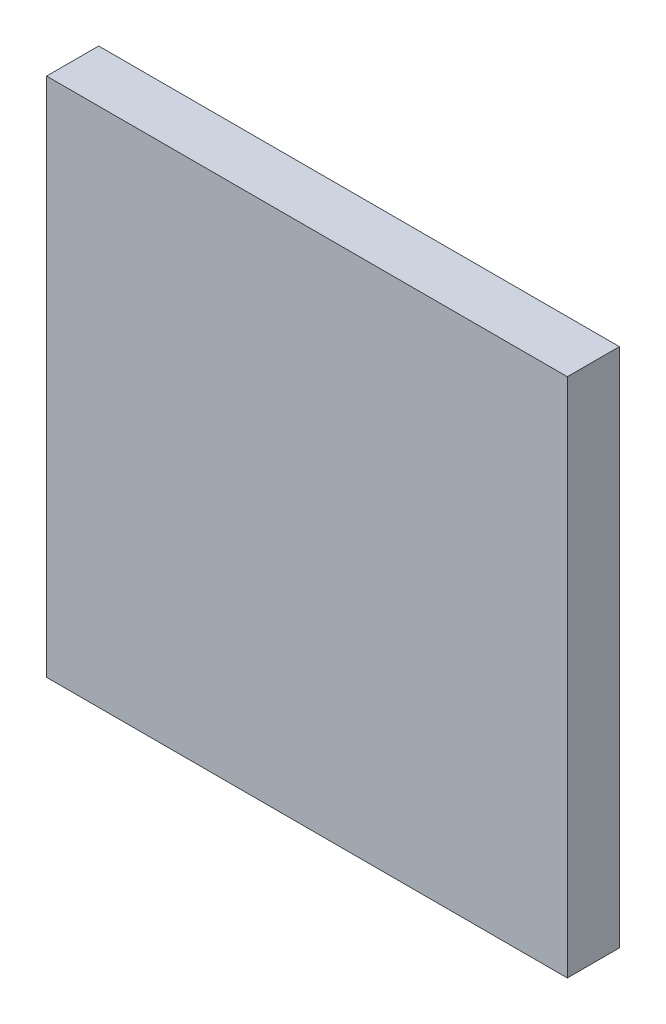
SolidWorks part; units mm, degrees
ref_plane "正面" through (0, 0, 0) normal (0, 0, 1) x (1, 0, 0)
ref_plane "平面" through (0, 0, 0) normal (0, 1, 0) x (1, 0, 0)
ref_plane "右側面" through (0, 0, 0) normal (1, 0, 0) x (0, 0, -1)
sketch "ｽｹｯﾁ1" plane through (0, 0, 0) normal (0, 0, 1) x (1, 0, 0)
  line L1 (-50.2232, -8.8808) -> (49.7768, -8.8808)
  line L2 (-50.2232, -8.8808) -> (-50.2232, 91.1192)
  line L3 (-50.2232, 91.1192) -> (49.7768, 91.1192)
  line L4 (49.7768, -8.8808) -> (49.7768, 91.1192)
  dimension "D1" = 100
  dimension "100" = 100
  dimension "D2" = 100
  dimension "D3" = 100
  dimension "D4" = 90
extrude "ﾎﾞｽ - 押し出し1" add sketch "ｽｹｯﾁ1" along normal blind 10 contours L2 L3 L4 L1
